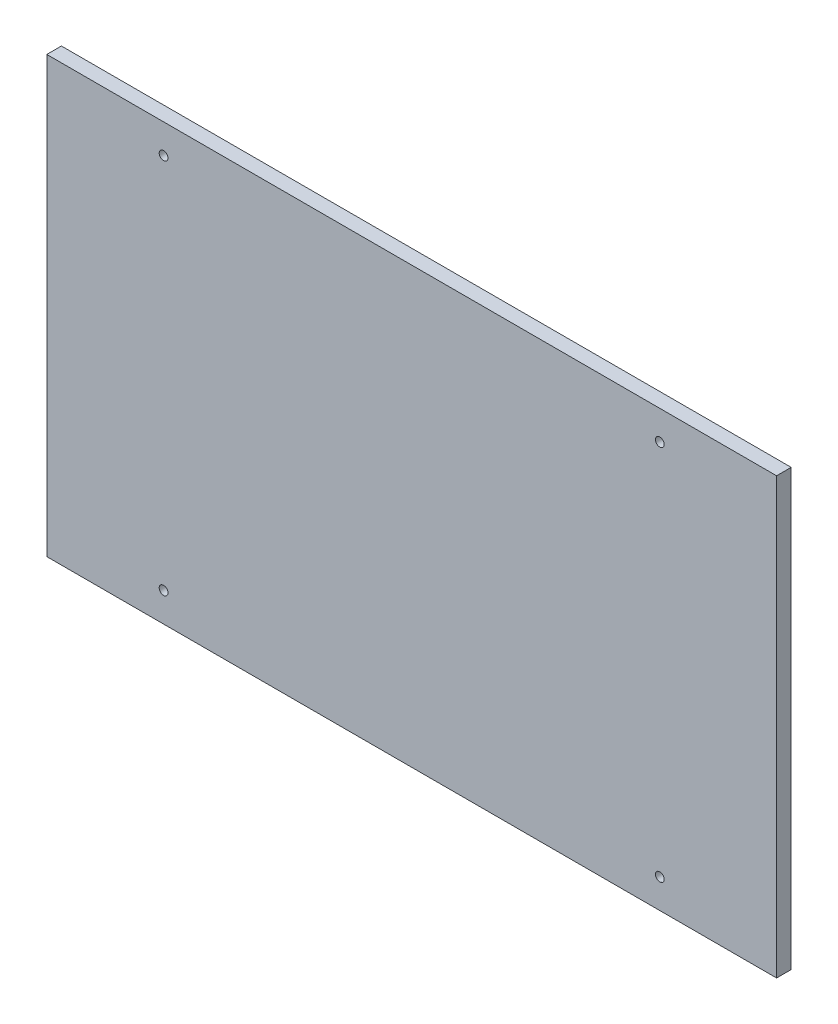
SolidWorks part; units mm, degrees
ref_plane "Plan de face" through (0, 0, 0) normal (0, 0, 1) x (1, 0, 0)
ref_plane "Plan de dessus" through (0, 0, 0) normal (0, 1, 0) x (1, 0, 0)
ref_plane "Plan de droite" through (0, 0, 0) normal (1, 0, 0) x (0, 0, -1)
sketch "Esquisse1" plane through (0, 0, 0) normal (0, 0, 1) x (1, 0, 0)
  line L1 (-125, 74.5) -> (125, 74.5)
  line L2 (-125, 74.5) -> (-125, -74.5)
  line L3 (-125, -74.5) -> (125, -74.5)
  line L4 (125, 74.5) -> (125, -74.5)
  line L5 (-125, 74.5) -> (125, -74.5) construction
  line L6 (-125, -74.5) -> (125, 74.5) construction
  point P0 (0, 0)
  dimension "D1" = 149
  dimension "D2" = 250
extrude "Boss.-Extru.1" add sketch "Esquisse1" along normal blind 5
sketch "Esquisse2" plane through (0, 0, 5) normal (0, 0, 1) x (1, 0, 0)
  line L0 (-125, 74.5) -> (-125, -74.5) construction
  line L1 (125, 74.5) -> (-125, 74.5) construction
  line L2 (-125, 0) -> (125, 0) construction
  line L3 (125, -74.5) -> (125, 74.5) construction
  line L4 (0, 74.5) -> (0, -74.5) construction
  line L5 (-125, -74.5) -> (125, -74.5) construction
  circle A0 centre (-85, 64.5) radius 1.5
  circle A1 centre (-85, -64.5) radius 1.5
  circle A2 centre (-85, 64.5) radius 1.5
  circle A3 centre (-85, -64.5) radius 1.5
  circle A4 centre (85, -64.5) radius 1.5
  circle A5 centre (85, 64.5) radius 1.5
  circle A6 centre (85, -64.5) radius 1.5
  circle A7 centre (85, 64.5) radius 1.5
  dimension "D1" = 3
  dimension "D3" = 10
  dimension "D2" = 40
extrude "Enlèv. mat.-Extru.2" cut sketch "Esquisse2" against normal blind 5 contours A0 | A1 | A4 | A5
